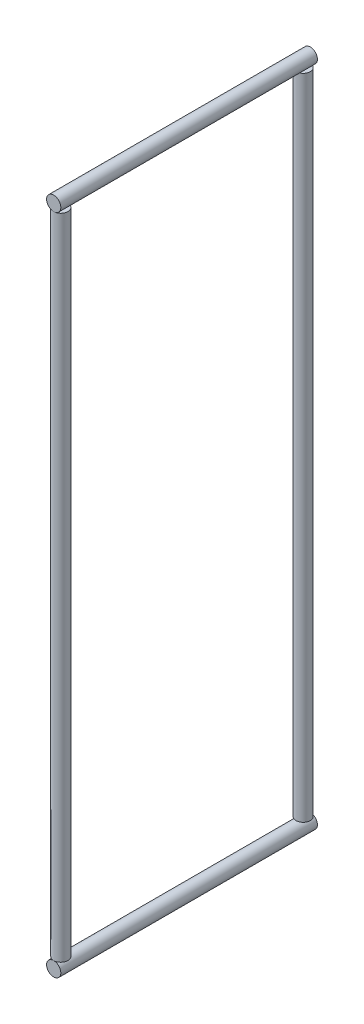
SolidWorks part; units mm, degrees
material "Magnesium Alloy"
ref_plane "Front Plane" through (0, 0, 0) normal (0, 0, 1) x (1, 0, 0)
ref_plane "Top Plane" through (0, 0, 0) normal (0, 1, 0) x (1, 0, 0)
ref_plane "Right Plane" through (0, 0, 0) normal (1, 0, 0) x (0, 0, -1)
sketch "Sketch1" plane through (0, 0, 0) normal (0, 0, 1) x (1, 0, 0)
  circle A0 centre (0, 0) radius 3.175
  dimension "D1" = 6.35
extrude "Boss-Extrude1" add sketch "Sketch1" along normal blind 114.3 contours A0
ref_plane "Plane1" through (0, 0, 9.525) normal (0, 0, 1) x (1, 0, 0)
ref_plane "Plane2" through (0, 3.175, 0) normal (0, 1, 0) x (1, 0, 0)
sketch "Sketch3" plane through (0, 3.175, 0) normal (0, 1, 0) x (1, 0, 0)
  line L0 (-3.175, -114.3) -> (3.175, -114.3) construction
  line L1 (-3.175, 0) -> (-3.175, -114.3) construction
  circle A0 centre (0, -111.125) radius 3.175
  dimension "D1" = 6.35
  dimension "D2" = 3.175
  dimension "D3" = 3.175
extrude "Boss-Extrude3" add sketch "Sketch3" along normal blind 288.925 separate body
sketch "Sketch4" plane through (0, 3.175, 0) normal (0, 1, 0) x (1, 0, 0)
  line L0 (3.175, 0) -> (-3.175, 0) construction
  line L1 (3.175, -114.3) -> (3.175, 0) construction
  circle A0 centre (0, -3.175) radius 3.175
  dimension "D1" = 6.35
  dimension "D2" = 3.175
  dimension "D3" = 3.175
extrude "Boss-Extrude4" add sketch "Sketch4" along normal blind 288.925 separate body
ref_plane "Plane3" through (0, 147.6375, 0) normal (0, 1, 0) x (1, 0, 0)
sketch "Sketch5" plane through (0, 0, 0) normal (0, 0, 1) x (1, 0, 0)
  line L0 (3.175, 292.1) -> (-3.175, 292.1) construction
  line L1 (3.175, 3.175) -> (3.175, 292.1) construction
  circle A0 centre (0, 295.275) radius 3.175
  dimension "D1" = 6.35
  dimension "D2" = 3.175
  dimension "D3" = 3.175
extrude "Boss-Extrude5" add sketch "Sketch5" along normal blind 114.3 separate body
